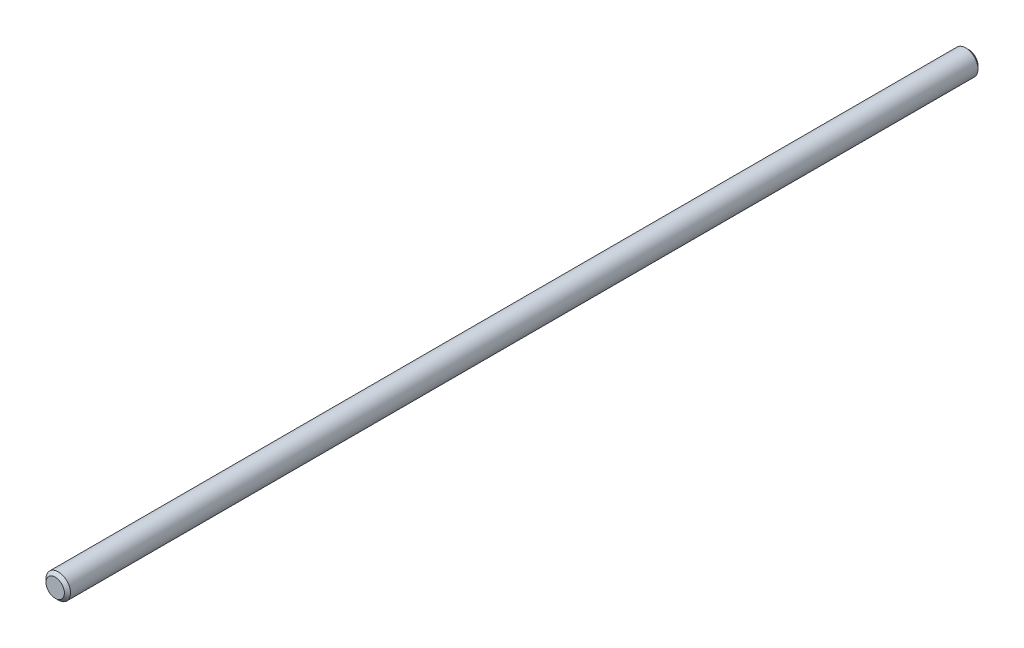
SolidWorks part; units mm, degrees
ref_plane "Ön Düzlem" through (0, 0, 0) normal (0, 0, 1) x (1, 0, 0)
ref_plane "Üst Düzlem" through (0, 0, 0) normal (0, 1, 0) x (1, 0, 0)
ref_plane "Sağ Düzlem" through (0, 0, 0) normal (1, 0, 0) x (0, 0, -1)
sketch "Sketch1" plane through (0, 0, 0) normal (0, 0, 1) x (1, 0, 0)
  circle A0 centre (0, 0) radius 4
  dimension "D1" = 8
extrude "Boss-Extrude1" add sketch "Sketch1" along normal blind 298
chamfer "Chamfer1" distance 1 angle 45 2 edges at (4, 0, 298) (4, 0, 0)
